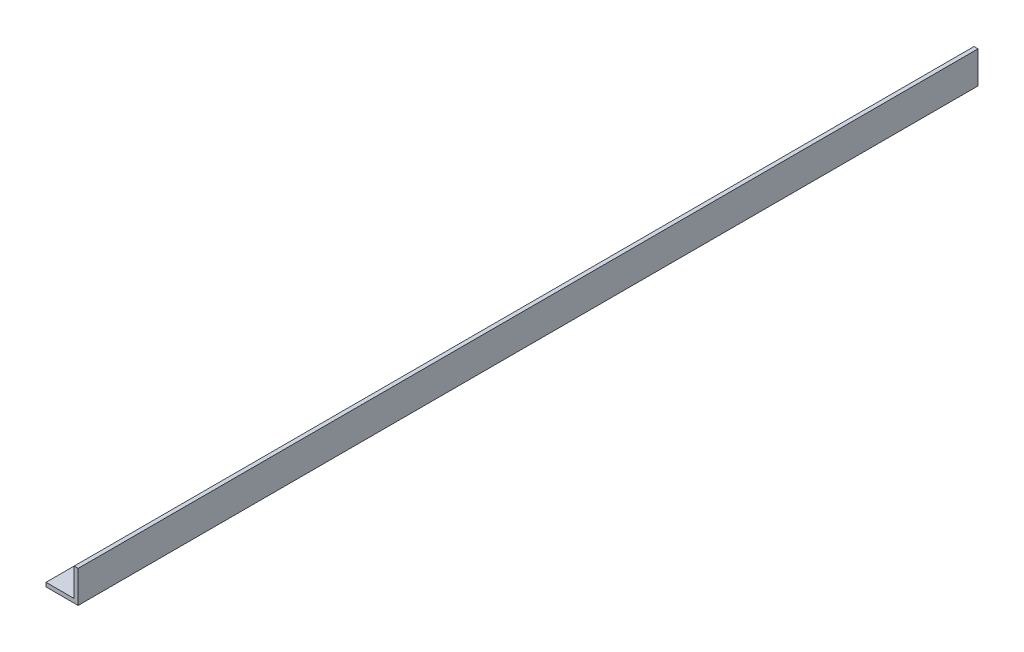
SolidWorks part; units mm, degrees
ref_plane "Front Plane" through (0, 0, 0) normal (0, 0, 1) x (1, 0, 0)
ref_plane "Top Plane" through (0, 0, 0) normal (0, 1, 0) x (1, 0, 0)
ref_plane "Right Plane" through (0, 0, 0) normal (1, 0, 0) x (0, 0, -1)
sketch "Sketch2" plane through (0, 0, 0) normal (0, 0, 1) x (1, 0, 0)
  line L0 (0, 0) -> (-12.7, 0)
  line L1 (-12.7, 0) -> (-12.7, 1.5875)
  line L2 (-12.7, 1.5875) -> (-1.5875, 1.5875)
  line L3 (-1.5875, 1.5875) -> (-1.5875, 12.7)
  line L4 (-1.5875, 12.7) -> (0, 12.7)
  line L5 (0, 12.7) -> (0, 0)
  dimension "D1" = 1.5875
  dimension "D2" = 12.7
extrude "Boss-Extrude1" add sketch "Sketch2" along normal blind 355.6
